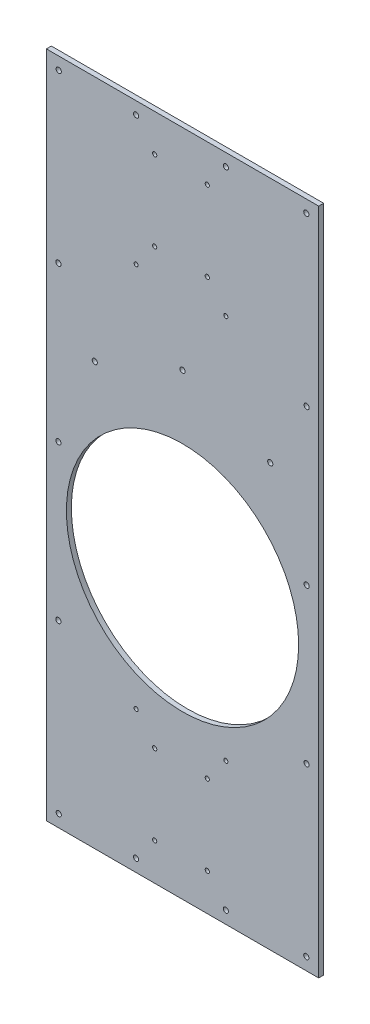
SolidWorks part; units mm, degrees
material "Thornel Mat VMA"
ref_plane "Front" through (0, 0, 0) normal (0, 0, 1) x (1, 0, 0)
ref_plane "Top" through (0, 0, 0) normal (0, 1, 0) x (1, 0, 0)
ref_plane "Right" through (0, 0, 0) normal (1, 0, 0) x (0, 0, -1)
sketch "草图1" plane through (0, 0, 0) normal (0, 0, 1) x (1, 0, 0)
  line L0 (110, 0) -> (48.3848, 0) construction
  line L1 (-110, -270) -> (110, -270)
  line L2 (-110, -270) -> (-110, 270)
  line L3 (-110, 270) -> (110, 270)
  line L4 (110, -270) -> (110, 270)
  line L5 (0, 270) -> (0, 178.268) construction
  point P0 (0, 0)
  dimension "D1" = 220
  dimension "D2" = 540
extrude "凸台-拉伸1" add sketch "草图1" along normal blind 4
sketch "草图2" plane through (0, 0, 0) normal (0, 0, -1) x (-1, 0, 0)
  line L0 (-110, 0) -> (110, 0) construction
  line L1 (-110, -270) -> (-110, 270) construction
  line L2 (110, 270) -> (110, -270) construction
  line L3 (110, -270) -> (-110, -270) construction
  circle A2 centre (100, -260) radius 2.1
  circle A3 centre (-100, -260) radius 2.1
  circle A6 centre (100, 260) radius 2.1
  circle A7 centre (-100, 260) radius 2.1
  circle A8 centre (-35, -260) radius 2.1
  circle A11 centre (-35, 260) radius 2.1
  circle A21 centre (37.5, 260) radius 2.1
  circle A22 centre (37.5, -260) radius 2.1
  dimension "D1" = 65
  dimension "D2" = 4.2
  dimension "D3" = 72.5
  dimension "D4" = 4.2
  dimension "D5" = 10
  dimension "D6" = 10
  dimension "D7" = 4.2
  dimension "D8" = 10
  dimension "D9" = 10
extrude "切除-拉伸1" cut sketch "草图2" against normal through all
sketch "草图3" plane through (0, 0, 4) normal (0, 0, 1) x (1, 0, 0)
  line L1 (110, -270) -> (110, 270) construction
  circle A0 centre (100, 30) radius 1.5
  circle A1 centre (100, -30) radius 1.5
  dimension "D1" = 3
  dimension "D2" = 10
  dimension "D3" = 30
  dimension "D4" = 3
  dimension "D5" = 30
  dimension "D6" = 10
sketch "草图4" plane through (0, 0, 4) normal (0, 0, 1) x (1, 0, 0)
  line L0 (110, 270) -> (-110, 270) construction
  line L1 (110, -270) -> (110, 270) construction
  circle A0 centre (0, -45) radius 93.8
  dimension "D1" = 187.6
  dimension "D2" = 315
  dimension "D3" = 110
extrude "切除-拉伸2" cut sketch "草图4" against normal blind 10
sketch "草图5" plane through (0, 0, 4) normal (0, 0, 1) x (1, 0, 0)
  line L0 (0, 0) -> (-32.216, 0) construction
  line L1 (0, 0) -> (0, -48.5775) construction
  line L6 (-110, -270) -> (110, -270) construction
  line L7 (110, -270) -> (110, 270) construction
  circle A0 centre (0, 0) radius 100.25 construction
  circle A2 centre (-100.25, 0) radius 2.1
  circle A4 centre (-70.8875, 70.8875) radius 2.1
  circle A5 centre (0, 100.25) radius 2.1
  circle A6 centre (70.8875, 70.8875) radius 2.1
  circle A7 centre (100.25, 0) radius 2.1
  circle A8 centre (70.8875, -70.8875) radius 2.1
  circle A9 centre (0, -100.25) radius 2.1
  circle A10 centre (-70.8875, -70.8875) radius 2.1
  circle A11 centre (-100.25, -125) radius 2.1
  circle A12 centre (100.25, -125) radius 2.1
  circle A13 centre (-100.25, 125) radius 2.1
  circle A14 centre (100.25, 125) radius 2.1
  point P22 (0, 0)
  dimension "D1" = 4.2
  dimension "D3" = 270
  dimension "D4" = 4.2
  dimension "D5" = 250
  dimension "D7" = 200.5
  dimension "D8" = 110
  dimension "D2" = 8
extrude "切除-拉伸3" cut sketch "草图5" against normal blind 10
sketch "草图6" plane through (0, 0, 0) normal (0, 0, -1) x (-1, 0, 0)
  line L4 (-110, 270) -> (-110, -270)
  line L5 (-110, -270) -> (110, -270)
  line L6 (110, -270) -> (110, 270)
  line L7 (110, 270) -> (-110, 270)
  line L8 (-110, 270) -> (-110, -270)
  line L9 (-110, -270) -> (110, -270)
  line L10 (110, -270) -> (110, 270)
  line L11 (110, 270) -> (-110, 270)
  circle A0 centre (37.5, 155.5256) radius 1.65 construction
  circle A1 centre (22.5, 175.5256) radius 1.7 construction
  circle A2 centre (-20, 175.5256) radius 1.7 construction
  circle A3 centre (-35, 155.5256) radius 1.65 construction
  circle A4 centre (-20, 240) radius 1.7 construction
  circle A5 centre (22.5, 240) radius 1.7 construction
  circle A6 centre (37.5, 155.5256) radius 1.65
  circle A7 centre (22.5, 175.5256) radius 1.7
  circle A8 centre (-20, 175.5256) radius 1.7
  circle A9 centre (-35, 155.5256) radius 1.65
  circle A10 centre (-20, 240) radius 1.7
  circle A11 centre (22.5, 240) radius 1.7
  dimension "D1" = 0
extrude "切除-拉伸5" cut sketch "草图6" against normal through all contours A11 | A10 | A7 | A8 | A9 | A6
mirror "镜向1" about plane through (0, 0, 0) normal (0, 1, 0) of "切除-拉伸5"
